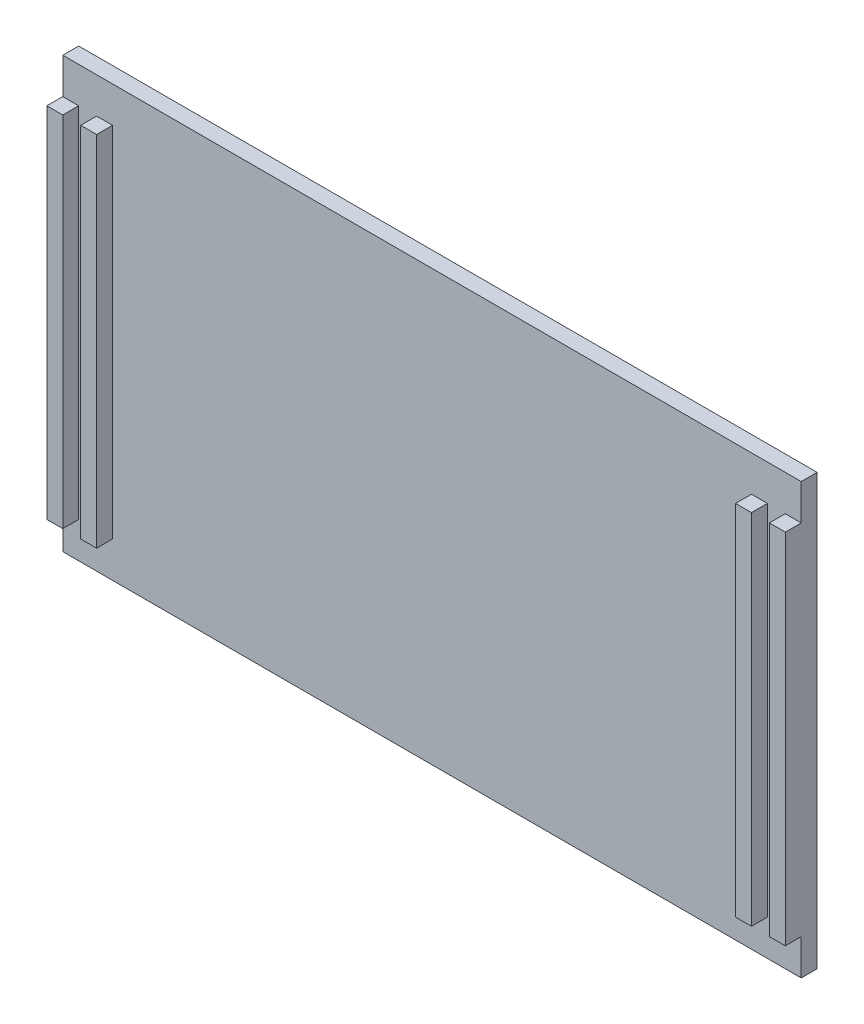
SolidWorks part; units mm, degrees
ref_plane "Front Plane" through (0, 0, 0) normal (0, 0, 1) x (1, 0, 0)
ref_plane "Top Plane" through (0, 0, 0) normal (0, 1, 0) x (1, 0, 0)
ref_plane "Right Plane" through (0, 0, 0) normal (1, 0, 0) x (0, 0, -1)
sketch "Sketch1" plane through (0, 0, 0) normal (0, 1, 0) x (1, 0, 0)
  line L0 (-63.4089, 20.488) -> (122.0911, 20.488)
  line L1 (122.0911, 20.488) -> (122.0911, 12.488)
  line L2 (122.0911, 12.488) -> (118.0911, 12.488)
  line L3 (118.0911, 12.488) -> (118.0911, 16.488)
  line L4 (118.0911, 16.488) -> (113.5911, 16.488)
  line L5 (113.5911, 16.488) -> (113.5911, 12.488)
  line L6 (113.5911, 12.488) -> (109.5911, 12.488)
  line L7 (109.5911, 12.488) -> (109.5911, 16.488)
  line L8 (-63.4089, 20.488) -> (-63.4089, 12.488)
  line L9 (-63.4089, 12.488) -> (-59.4089, 12.488)
  line L10 (-59.4089, 12.488) -> (-59.4089, 16.488)
  line L11 (-59.4089, 16.488) -> (-54.9089, 16.488)
  line L12 (-54.9089, 16.488) -> (-54.9089, 12.488)
  line L13 (-54.9089, 12.488) -> (-50.9089, 12.488)
  line L14 (-50.9089, 12.488) -> (-50.9089, 16.488)
  line L15 (-50.9089, 16.488) -> (109.5911, 16.488)
extrude "Boss-Extrude1" add sketch "Sketch1" along normal mid plane 108
sketch "Sketch7" plane through (0, 0, -12.488) normal (0, 0, 1) x (1, 0, 0)
  line L1 (122.0911, 54) -> (-63.4089, 54)
  line L2 (122.0911, 54) -> (122.0911, 45)
  line L3 (122.0911, 45) -> (-63.4089, 45)
  line L4 (-63.4089, 54) -> (-63.4089, 45)
extrude "Cut-Extrude4" cut sketch "Sketch7" against normal up to surface (4 mm away) up to face at (29.3411, 0, -16.488)
sketch "Sketch8" plane through (0, 0, -12.488) normal (0, 0, 1) x (1, 0, 0)
  line L1 (122.0911, -54) -> (-63.4089, -54)
  line L2 (122.0911, -54) -> (122.0911, -45)
  line L3 (122.0911, -45) -> (-63.4089, -45)
  line L4 (-63.4089, -54) -> (-63.4089, -45)
extrude "Cut-Extrude5" cut sketch "Sketch8" against normal up to surface (4 mm away) up to face at (29.3411, 9, -16.488)
